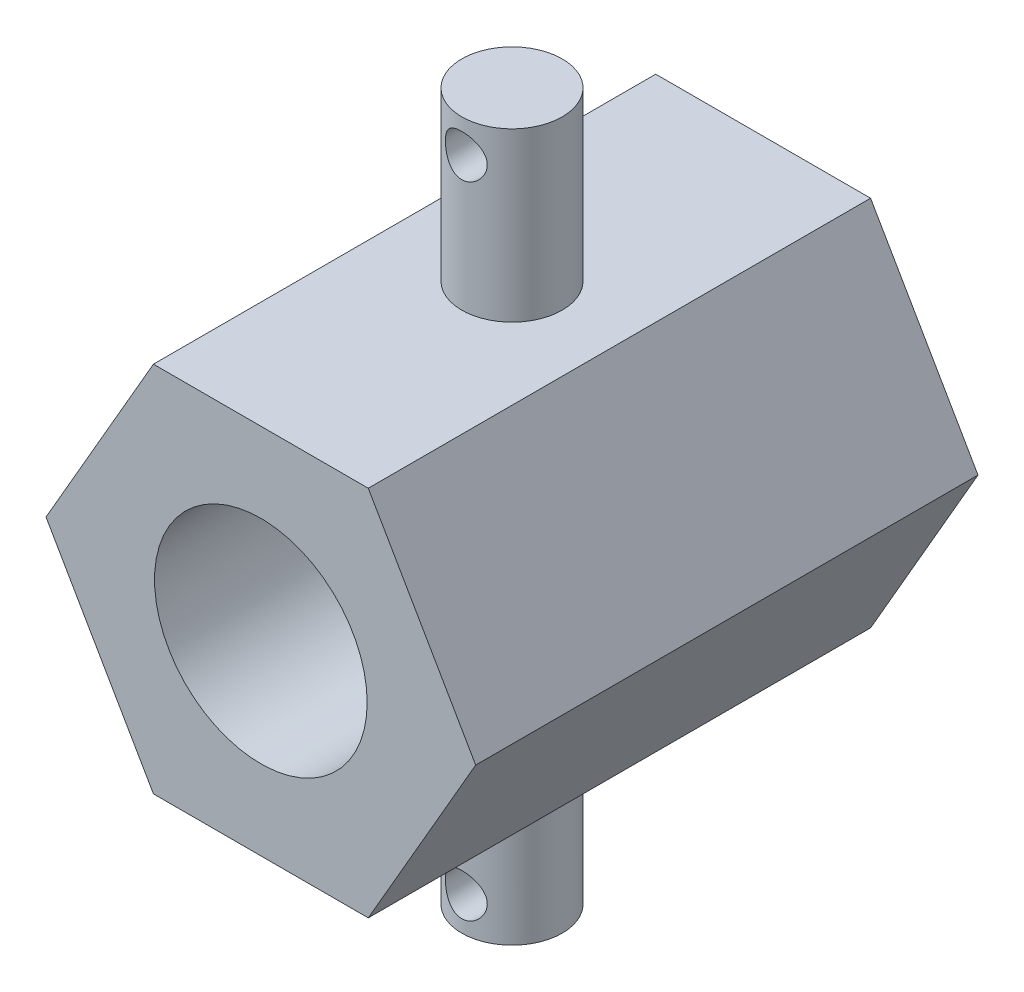
SolidWorks part; units mm, degrees
ref_plane "Front Plane" through (0, 0, 0) normal (0, 0, 1) x (1, 0, 0)
ref_plane "Top Plane" through (0, 0, 0) normal (0, 1, 0) x (1, 0, 0)
ref_plane "Right Plane" through (0, 0, 0) normal (1, 0, 0) x (0, 0, -1)
sketch "Sketch1" plane through (0, 0, 0) normal (0, 0, 1) x (1, 0, 0)
  line L1 (6.4158, -11.1125) -> (12.8316, 0)
  line L2 (12.8316, 0) -> (6.4158, 11.1125)
  line L3 (6.4158, 11.1125) -> (-6.4158, 11.1125)
  line L4 (-6.4158, 11.1125) -> (-12.8316, 0)
  line L5 (-12.8316, 0) -> (-6.4158, -11.1125)
  line L6 (-6.4158, -11.1125) -> (6.4158, -11.1125)
  circle A0 centre (0, 0) radius 11.1125 construction
  circle A1 centre (0, 0) radius 6.35
  dimension "D2" = 12.7
  dimension "D1" = 22.225
extrude "Boss-Extrude1" add sketch "Sketch1" along normal blind 30
sketch "Sketch2" plane through (0, -11.1125, 0) normal (0, -1, 0) x (1, 0, 0)
  line L0 (-6.4158, 30) -> (6.4158, 30) construction
  line L2 (6.4158, 30) -> (6.4158, 0) construction
  circle A0 centre (0, 15) radius 3
  point P5 (0, 30)
  point P11 (6.4158, 15)
  dimension "D1" = 6
extrude "Boss-Extrude2" add sketch "Sketch2" along normal blind 10
sketch "Sketch3" plane through (0, 0, 0) normal (0, 0, 1) x (1, 0, 0)
  line L0 (-6.4158, -11.1125) -> (6.4158, -11.1125) construction
  line L1 (-3, -21.1125) -> (3, -21.1125) construction
  circle A0 centre (0, -19.1125) radius 1.25
  point P5 (0, -11.1125)
  dimension "D1" = 2.5
  dimension "D2" = 2
extrude "Cut-Extrude1" cut sketch "Sketch3" along normal through all
mirror "Mirror1" about plane through (0, 0, 0) normal (0, 1, 0) of "Cut-Extrude1", "Boss-Extrude2"
